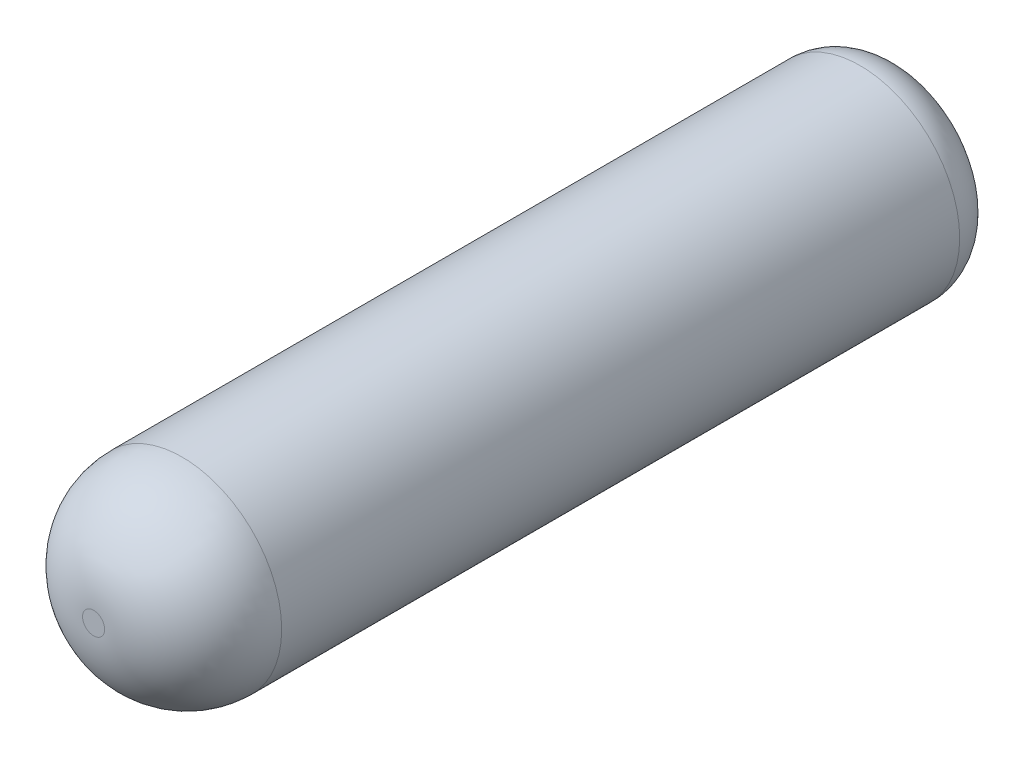
SolidWorks part; units mm, degrees
ref_plane "Front Plane" through (0, 0, 0) normal (0, 0, 1) x (1, 0, 0)
ref_plane "Top Plane" through (0, 0, 0) normal (0, 1, 0) x (1, 0, 0)
ref_plane "Right Plane" through (0, 0, 0) normal (1, 0, 0) x (0, 0, -1)
sketch "Sketch1" plane through (0, 0, 0) normal (0, 0, 1) x (1, 0, 0)
  circle A0 centre (0, 0) radius 14.2875
  dimension "D1" = 28.575
extrude "Boss-Extrude1" add sketch "Sketch1" along normal blind 116.332
fillet "Fillet2" radius 6.35 1 edges at (14.2875, 0, 0)
fillet "Fillet3" radius 12.7 1 edges at (14.2875, 0, 116.332)
